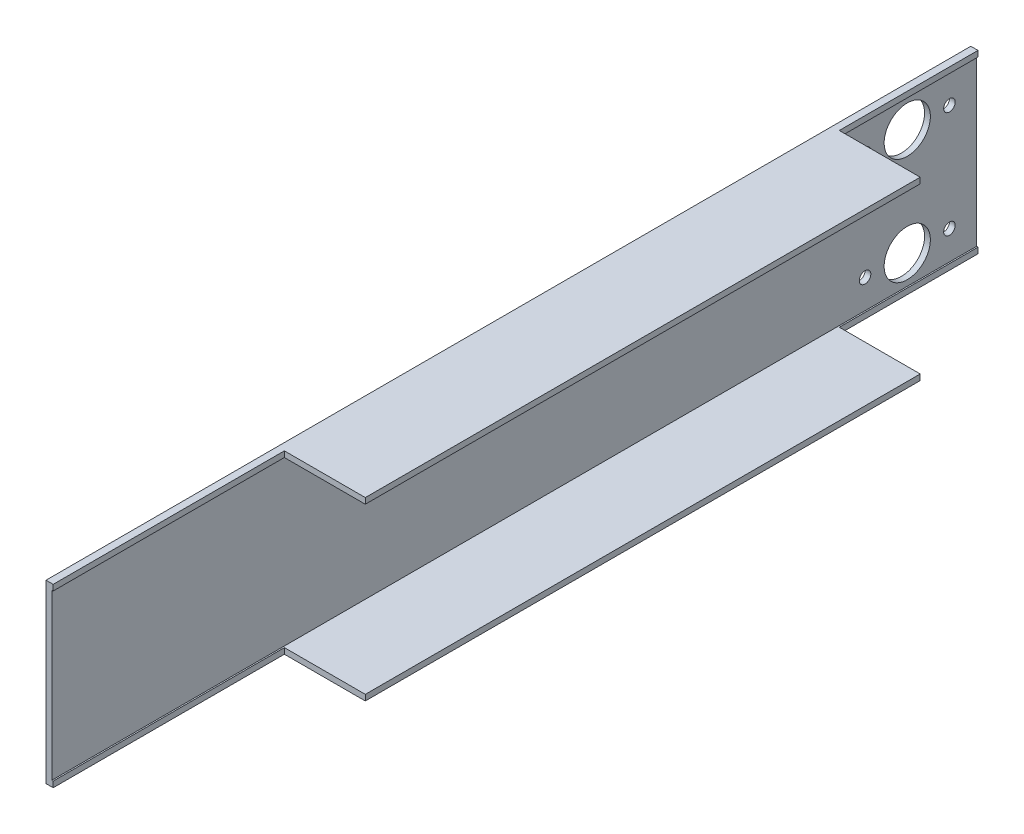
SolidWorks part; units mm, degrees
ref_plane "Plano frontal" through (0, 0, 0) normal (0, 0, 1) x (1, 0, 0)
ref_plane "Plano superior" through (0, 0, 0) normal (0, 1, 0) x (1, 0, 0)
ref_plane "Plano direito" through (0, 0, 0) normal (1, 0, 0) x (0, 0, -1)
sketch "Esboço2" plane through (0, 0, 0) normal (0, 0, 1) x (1, 0, 0)
  line L0 (0, 0) -> (0, 76.2)
  line L1 (0, 76.2) -> (38.1, 76.2)
  line L2 (38.1, 76.2) -> (38.1, 73.7)
  line L3 (38.1, 73.7) -> (2.5, 73.7)
  line L4 (2.5, 73.7) -> (2.5, 2.5)
  line L5 (2.5, 2.5) -> (38.1, 2.5)
  line L6 (38.1, 2.5) -> (38.1, 0)
  line L7 (38.1, 0) -> (0, 0)
  dimension "D1" = 76.2
  dimension "D2" = 38.1
  dimension "D3" = 2.5
  dimension "D4" = 2.5
  dimension "D5" = 2.5
extrude "Ressalto-extrusão1" add sketch "Esboço2" along normal blind 400
sketch "Esboço3" plane through (0, 0, 0) normal (-1, 0, 0) x (0, 0, 1)
  line L0 (0, 0) -> (0, 63.5852) construction
  line L1 (0, 15) -> (30, 15) construction
  line L2 (0, 38.1) -> (-21.2286, 38.1) construction
  line L3 (0, 76.2) -> (0, 0) construction
  line L4 (30, 15) -> (30, 6.7336) construction
  circle A0 centre (30, 15) radius 10
  circle A1 centre (30, 61.2) radius 10
  circle A2 centre (11.75, 15) radius 2.5
  circle A3 centre (48.25, 15) radius 2.5
  circle A4 centre (48.25, 61.2) radius 2.5
  circle A5 centre (11.75, 61.2) radius 2.5
  dimension "D2" = 20
  dimension "D5" = 5
  dimension "D1" = 15
  dimension "D3" = 30
  dimension "D4" = 18.25
extrude "Corte-extrusão1" cut sketch "Esboço3" against normal through all
sketch "Esboço4" plane through (0, 0, 0) normal (0, -1, 0) x (1, 0, 0)
  line L1 (38.1, 0) -> (3.1, 0)
  line L2 (38.1, 0) -> (38.1, 60)
  line L3 (38.1, 60) -> (3.1, 60)
  line L4 (3.1, 0) -> (3.1, 60)
  line L5 (38.1, 400) -> (3.1, 400)
  line L6 (38.1, 400) -> (38.1, 300)
  line L7 (38.1, 300) -> (3.1, 300)
  line L8 (3.1, 400) -> (3.1, 300)
  dimension "D1" = 35
  dimension "D2" = 60
  dimension "D3" = 35
  dimension "D4" = 100
extrude "Corte-extrusão2" cut sketch "Esboço4" against normal through all
